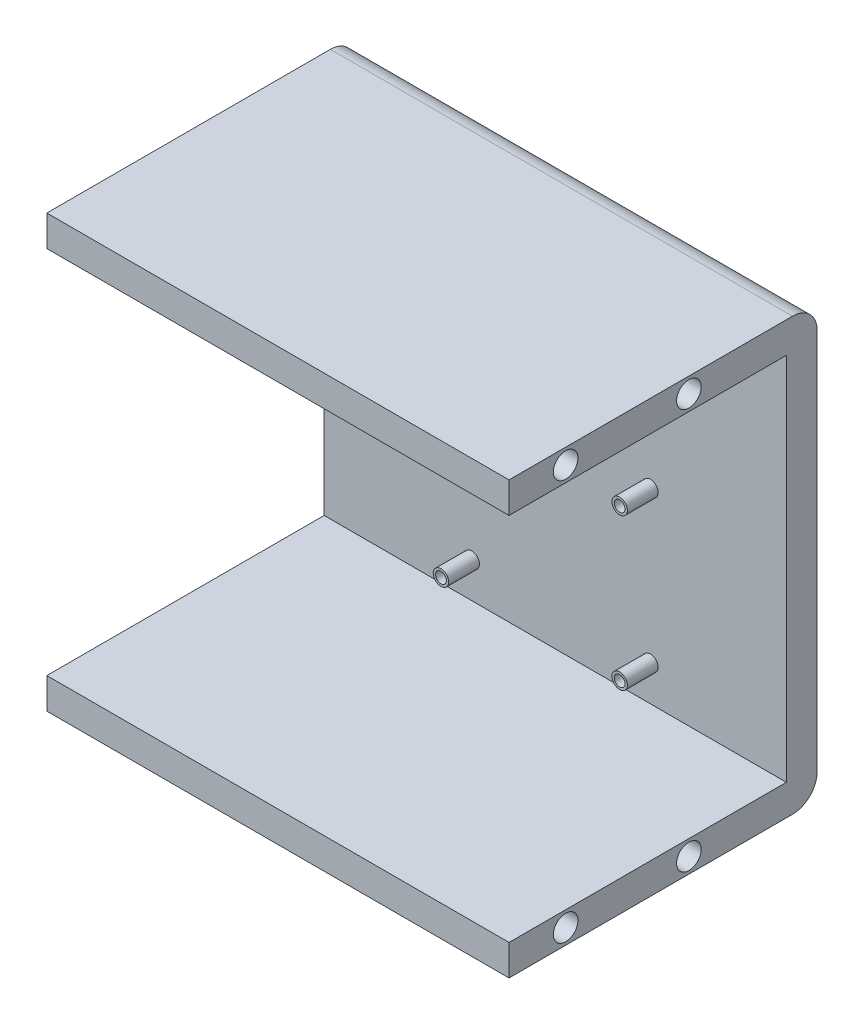
SolidWorks part; units mm, degrees
ref_plane "Front Plane" through (0, 0, 0) normal (0, 0, 1) x (1, 0, 0)
ref_plane "Top Plane" through (0, 0, 0) normal (0, 1, 0) x (1, 0, 0)
ref_plane "Right Plane" through (0, 0, 0) normal (1, 0, 0) x (0, 0, -1)
sketch "Sketch1" plane through (0, 0, 0) normal (0, 0, 1) x (1, 0, 0)
  line L1 (0, 60) -> (150, 60)
  line L2 (0, 60) -> (0, -60)
  line L3 (0, -60) -> (150, -60)
  line L4 (150, 60) -> (150, -60)
  line L5 (0, 60) -> (150, -60) construction
  line L6 (0, -60) -> (150, 60) construction
  point P0 (75, 0)
  point P5 (0, 0)
  dimension "D1" = 150
  dimension "D2" = 120
extrude "Boss-Extrude1" add sketch "Sketch1" along normal blind 10
sketch "Sketch2" plane through (0, 0, 0) normal (-1, 0, 0) x (0, 0, 1)
  line L0 (10, -60) -> (0, -60) construction
  line L2 (0, 60) -> (0, -60) construction
  circle A0 centre (5, 0) radius 4
  circle A1 centre (5, 30) radius 4
  circle A2 centre (5, -30) radius 4
  dimension "D1" = 8
  dimension "D2" = 30
  dimension "D3" = 30
  dimension "D4" = 30
  dimension "D5" = 5
extrude "Cut-Extrude1" cut sketch "Sketch2" against normal blind 30
sketch "Croquis4" plane through (0, 0, 10) normal (0, 0, 1) x (1, 0, 0)
  line L1 (0, -60) -> (150, -60) construction
  line L2 (150, -60) -> (150, 60) construction
  line L5 (150, 60) -> (0, 60) construction
  circle A0 centre (47.9001, 0.5) radius 2.5
  circle A1 centre (105.9, 0.6156) radius 2.5
  circle A2 centre (105.9, -48.5) radius 2.5
  circle A3 centre (47.9001, -48.5) radius 2.5
  dimension "D5" = 5
  dimension "D6" = 59.3844
  dimension "D1" = 57.9999
  dimension "D2" = 49
  dimension "D3" = 11.5
  dimension "D4" = 44.1
extrude "Saliente-Extruir2" add sketch "Croquis4" along normal blind 10
sketch "Croquis5" plane through (0, 0, 20) normal (0, 0, 1) x (1, 0, 0)
  circle A0 centre (47.9001, 0.5) radius 1.75
  circle A1 centre (47.9001, -48.5) radius 1.75
  circle A2 centre (105.9, -48.5) radius 1.75
  circle A3 centre (105.9, 0.6156) radius 1.75
  dimension "D1" = 3.5
extrude "Cortar-Extruir1" cut sketch "Croquis5" against normal blind 9
sketch "Croquis6" plane through (0, -60, 0) normal (0, -1, 0) x (1, 0, 0)
  line L1 (0, 0) -> (150, 0)
  line L2 (0, 0) -> (0, 100)
  line L3 (0, 100) -> (150, 100)
  line L4 (150, 0) -> (150, 100)
  dimension "D1" = 100
extrude "Saliente-Extruir3" add sketch "Croquis6" along normal blind 10
sketch "Croquis9" plane through (0, 60, 0) normal (0, 1, 0) x (1, 0, 0)
  line L1 (0, 0) -> (150, 0)
  line L2 (0, 0) -> (0, -100)
  line L3 (0, -100) -> (150, -100)
  line L4 (150, 0) -> (150, -100)
extrude "Saliente-Extruir4" add sketch "Croquis9" along normal blind 10
sketch "Croquis10" plane through (150, 0, 0) normal (1, 0, 0) x (0, 0, -1)
  line L0 (-100, 70) -> (-100, 60) construction
  line L1 (-100, -70) -> (-100, -60) construction
  line L3 (0, -70) -> (0, 70) construction
  circle A0 centre (-81.6267, 65) radius 4
  circle A1 centre (-41.6267, 65) radius 4
  circle A2 centre (-81.6267, -65) radius 4
  circle A3 centre (-41.6267, -65) radius 4
  point P16 (-100, 65)
  point P20 (-100, -65)
  dimension "D1" = 8
  dimension "D2" = 40
  dimension "D3" = 41.6267
extrude "Cortar-Extruir2" cut sketch "Croquis10" against normal blind 30
fillet "Fillet1" radius 8 2 edges at (75, 70, 0) (75, -70, 0)
